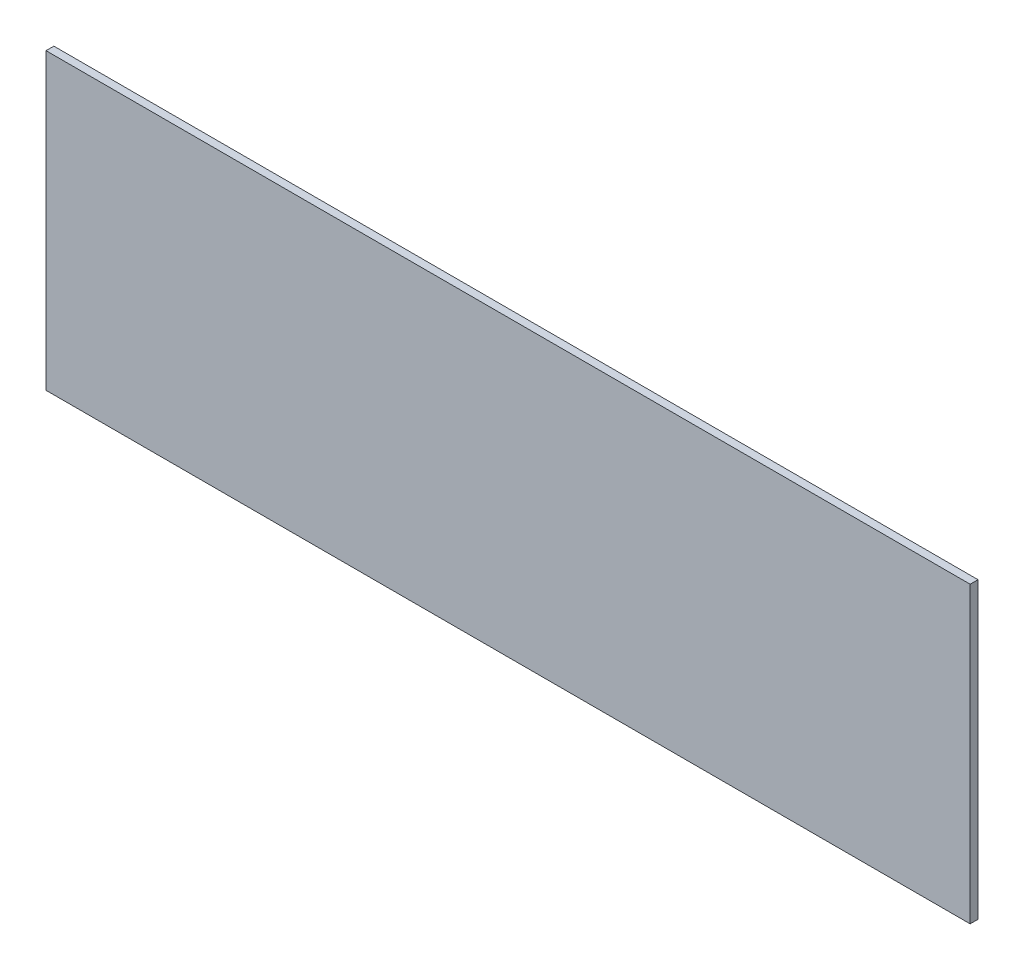
SolidWorks part; units mm, degrees
ref_plane "Front Plane" through (0, 0, 0) normal (0, 0, 1) x (1, 0, 0)
ref_plane "Top Plane" through (0, 0, 0) normal (0, 1, 0) x (1, 0, 0)
ref_plane "Right Plane" through (0, 0, 0) normal (1, 0, 0) x (0, 0, -1)
sketch "Sketch1" plane through (0, 0, 0) normal (0, 0, 1) x (1, 0, 0)
  line L1 (94.25, -30) -> (-94.25, -30)
  line L2 (94.25, -30) -> (94.25, 30)
  line L3 (94.25, 30) -> (-94.25, 30)
  line L4 (-94.25, -30) -> (-94.25, 30)
  line L5 (94.25, -30) -> (-94.25, 30) construction
  line L6 (94.25, 30) -> (-94.25, -30) construction
  point P0 (0, 0)
  dimension "D1" = 60
  dimension "D2" = 188.5
extrude "Boss-Extrude1" add sketch "Sketch1" along normal blind 1.6
sketch "Sketch2"
sketch "Sketch3" plane through (0, 0, 0) normal (0, 0, -1) x (-1, 0, 0)
  line L0 (-62.8559, 0.0075) -> (62.8108, 0.0075) construction
